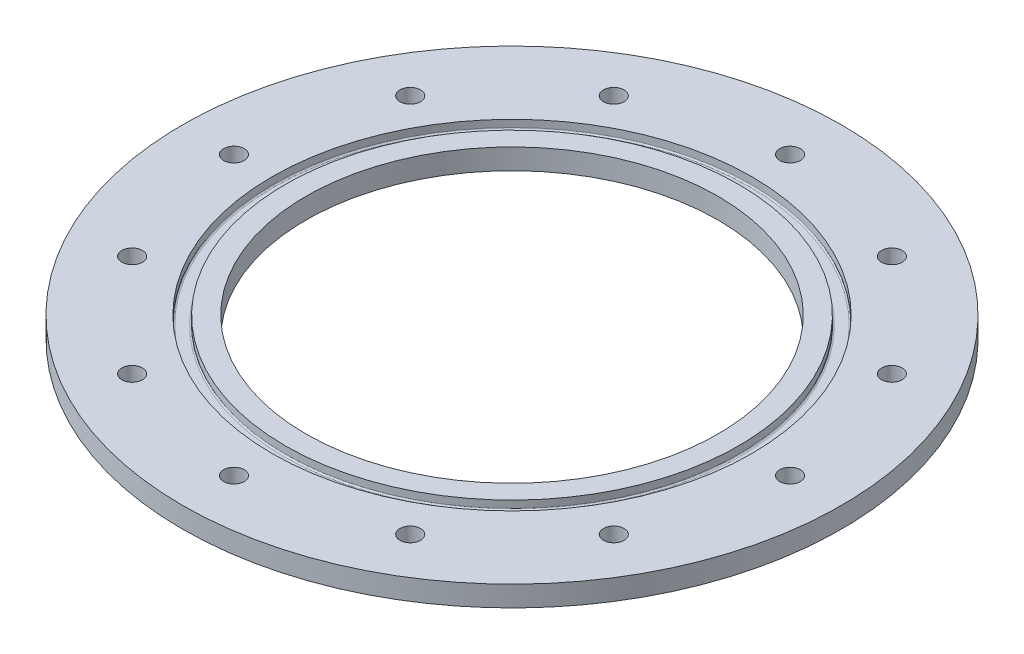
SolidWorks part; units mm, degrees
ref_plane "Front Plane" through (0, 0, 0) normal (0, 0, 1) x (1, 0, 0)
ref_plane "Top Plane" through (0, 0, 0) normal (0, 1, 0) x (1, 0, 0)
ref_plane "Right Plane" through (0, 0, 0) normal (1, 0, 0) x (0, 0, -1)
sketch "Sketch1" plane through (0, 0, 0) normal (0, 1, 0) x (1, 0, 0)
  circle A0 centre (0, 0) radius 101.6
  dimension "D1" = 203.2
extrude "Boss-Extrude1" add sketch "Sketch1" along normal blind 6.35
sketch "Sketch2" plane through (0, 6.35, 0) normal (0, 1, 0) x (1, 0, 0)
  circle A0 centre (0, 0) radius 63.5
  dimension "D1" = 127
extrude "Cut-Extrude1" cut sketch "Sketch2" against normal through all
sketch "Sketch3" plane through (0, 6.35, 0) normal (0, 1, 0) x (1, 0, 0)
  circle A0 centre (0, 0) radius 69.85
  circle A1 centre (0, 0) radius 85.725
  circle A2 centre (0, 85.725) radius 3.175
  circle A3 centre (42.8625, 74.24) radius 3.175
  circle A4 centre (74.24, 42.8625) radius 3.175
  circle A5 centre (85.725, 0) radius 3.175
  circle A6 centre (74.24, -42.8625) radius 3.175
  circle A7 centre (42.8625, -74.24) radius 3.175
  circle A8 centre (0, -85.725) radius 3.175
  circle A9 centre (-42.8625, -74.24) radius 3.175
  circle A10 centre (-74.24, -42.8625) radius 3.175
  circle A11 centre (-85.725, 0) radius 3.175
  circle A12 centre (-74.24, 42.8625) radius 3.175
  circle A13 centre (-42.8625, 74.24) radius 3.175
  point P30 (0, 0)
  dimension "D1" = 139.7
  dimension "D2" = 15.875
  dimension "D3" = 6.35
  dimension "D4" = 12
extrude "Cut-Extrude2" cut sketch "Sketch3" against normal up to next contours A12 | A13 | A3 | A4 | A5 | A6 | A7 | A8 | A9 | A10 | A11 | A2
sketch "Sketch4" plane through (0, 6.35, 0) normal (0, 1, 0) x (1, 0, 0)
  circle A0 centre (0, 0) radius 69.85
  circle A1 centre (0, 0) radius 73.9394
  dimension "D1" = 139.7
  dimension "D2" = 4.0894
extrude "Cut-Extrude3" cut sketch "Sketch4" against normal blind 2.6416
fillet "Fillet1" radius 0.4318 2 edges at (0, 3.7084, 73.9394) (0, 3.7084, 69.85)
equation "\"od\"= 8'flange disc outer diameter"
equation "\"D1@Sketch1\"=\"od\""
equation "\"gw\" = 0.161'groove width for O-ring"
equation "\"D2@Sketch4\"=\"gw\""
equation "\"gd\" = .104'groove depth for O-ring"
equation "\"D1@Cut-Extrude3\"=\"gd\""
equation "\"oid\"= 5.5'O-ring inner diameter"
equation "\"D1@Sketch4\"=\"oid\""
equation "\"gr\"= .017'groove radius"
equation "\"D1@Fillet1\"=\"gr\""
